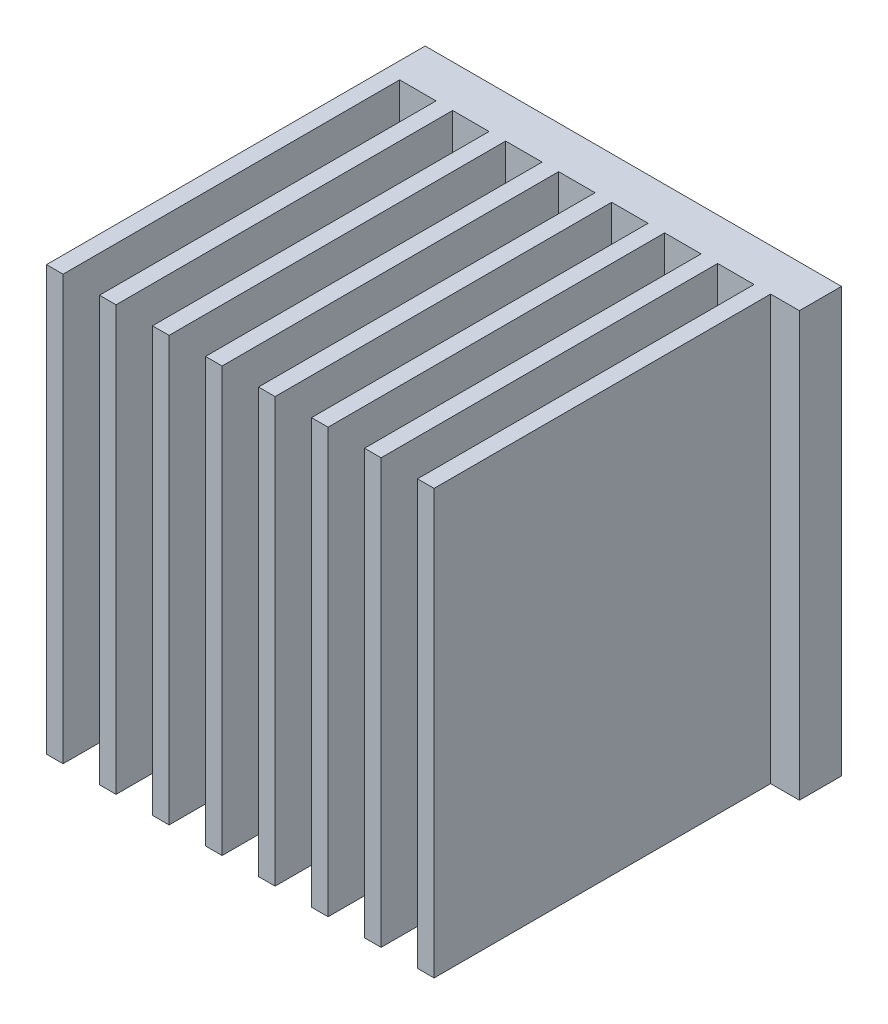
SolidWorks part; units mm, degrees
material "6063-T6"
ref_plane "X-Y Datum" through (0, 0, 0) normal (0, 0, 1) x (1, 0, 0)
ref_plane "X-Z Datum" through (0, 0, 0) normal (0, 1, 0) x (1, 0, 0)
ref_plane "Y-Z Datum" through (0, 0, 0) normal (1, 0, 0) x (0, 0, -1)
sketch "Sketch1" plane through (0, 0, 0) normal (0, 0, 1) x (1, 0, 0)
  line L1 (-15.71, -16) -> (15.71, -16)
  line L2 (-15.71, -16) -> (-15.71, 16)
  line L3 (-15.71, 16) -> (15.71, 16)
  line L4 (15.71, -16) -> (15.71, 16)
  line L5 (-15.71, -16) -> (15.71, 16) construction
  line L6 (-15.71, 16) -> (15.71, -16) construction
  point P0 (0, 0)
  dimension "D1" = 31.42
  dimension "D2" = 32
extrude "Boss-Extrude1" add sketch "Sketch1" along normal blind 3.175
sketch "Sketch2" plane through (0, 0, 3.175) normal (0, 0, 1) x (1, 0, 0)
  line L0 (-15.71, -16) -> (15.71, -16) construction
  line L1 (-15.71, 16) -> (-14.46, 16)
  line L2 (-15.71, 16) -> (-15.71, -16)
  line L3 (-15.71, -16) -> (-14.46, -16)
  line L4 (-14.46, 16) -> (-14.46, -16)
  dimension "D1" = 1.25
extrude "Boss-Extrude2" add sketch "Sketch2" along normal blind 25.4
pattern_linear "LPattern1" count 8 spacing 4 along (1, 0, 0) of "Boss-Extrude2"
